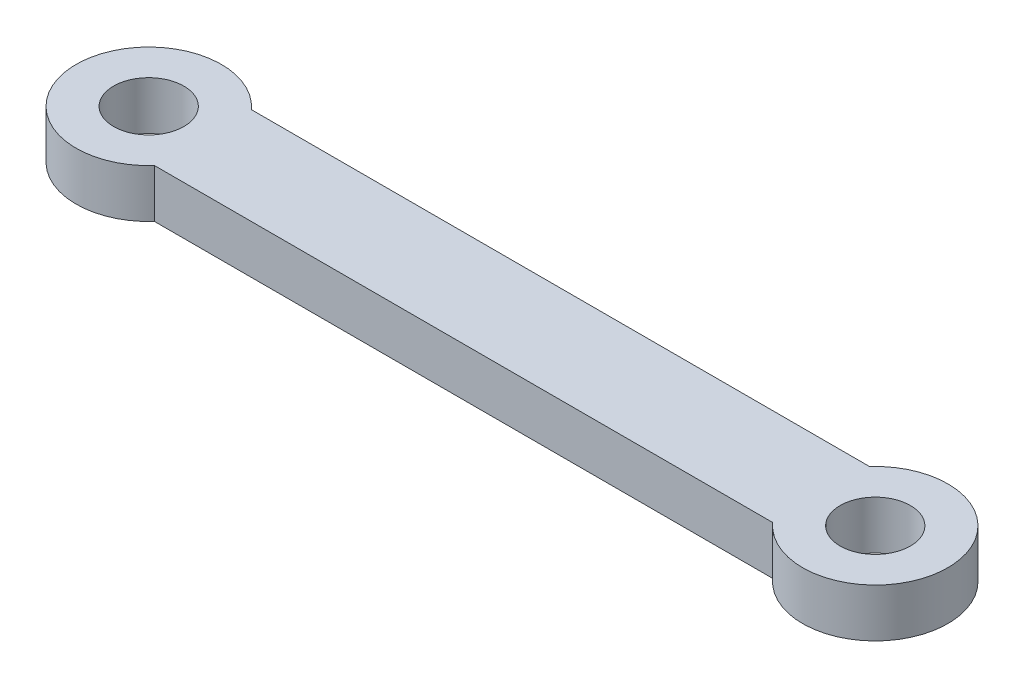
SolidWorks part; units mm, degrees
material "Aleación 6061"
ref_plane "Alzado" through (0, 0, 0) normal (0, 0, 1) x (1, 0, 0)
ref_plane "Planta" through (0, 0, 0) normal (0, 1, 0) x (1, 0, 0)
ref_plane "Vista lateral" through (0, 0, 0) normal (1, 0, 0) x (0, 0, -1)
sketch "Croquis base" plane through (0, 0, 0) normal (0, 1, 0) x (1, 0, 0)
  line L0 (-15, 0) -> (15, 0) construction
  line L4 (-12.7639, 2) -> (12.7639, 2)
  line L6 (-12.7639, -2) -> (12.7639, -2)
  arc A0 (-15, 3) -> (-15, -3) centre (-15, 0) ccw
  arc A1 (15, -3) -> (15, 3) centre (15, 0) ccw
  arc A2 (-12.7639, 2) -> (-12.7639, -2) centre (-15, 0) ccw
  arc A3 (12.7639, -2) -> (12.7639, 2) centre (15, 0) ccw
  point P2 (0, 0)
  point P8 (0, 0)
  dimension "D2" = 3
  dimension "D1" = 30
  dimension "D3" = 4
extrude "Saliente-Extruir1" add sketch "Croquis base" along normal blind 2
sketch "Croquis barrenos" plane through (0, 2, 0) normal (0, 1, 0) x (1, 0, 0)
  circle A0 centre (-15, 0) radius 1.45
  circle A1 centre (15, 0) radius 1.45
  dimension "D1" = 2.9
extrude "Cortar-Extruir1" cut sketch "Croquis barrenos" against normal blind 2
